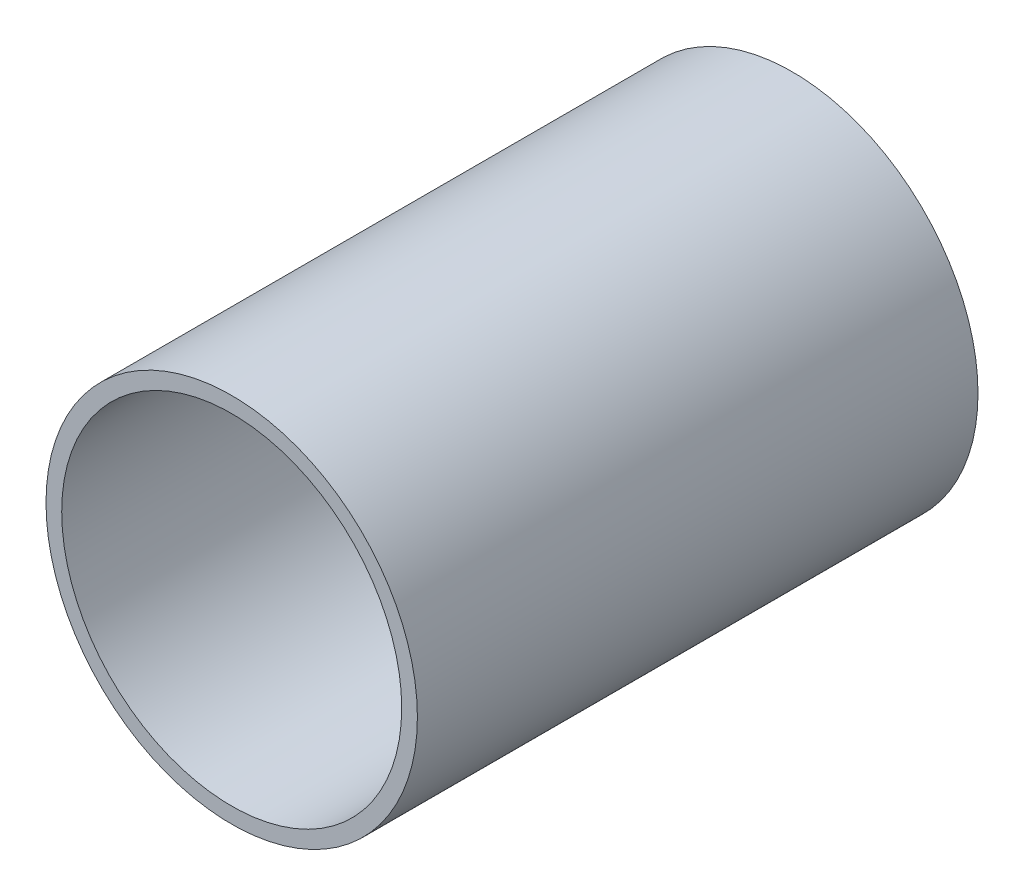
SolidWorks part; units mm, degrees
ref_plane "Plane1" through (0, 0, 0) normal (0, 0, 1) x (1, 0, 0)
ref_plane "Plane2" through (0, 0, 0) normal (0, 1, 0) x (1, 0, 0)
ref_plane "Plane3" through (0, 0, 0) normal (1, 0, 0) x (0, 0, -1)
sketch "Sketch1" plane through (0, 0, 0) normal (0, 0, 1) x (1, 0, 0)
  circle A0 centre (0, 0) radius 77.0255
  circle A1 centre (0, 0) radius 84.1375
extrude "BasePipe" add sketch "Sketch1" along normal mid plane 254
